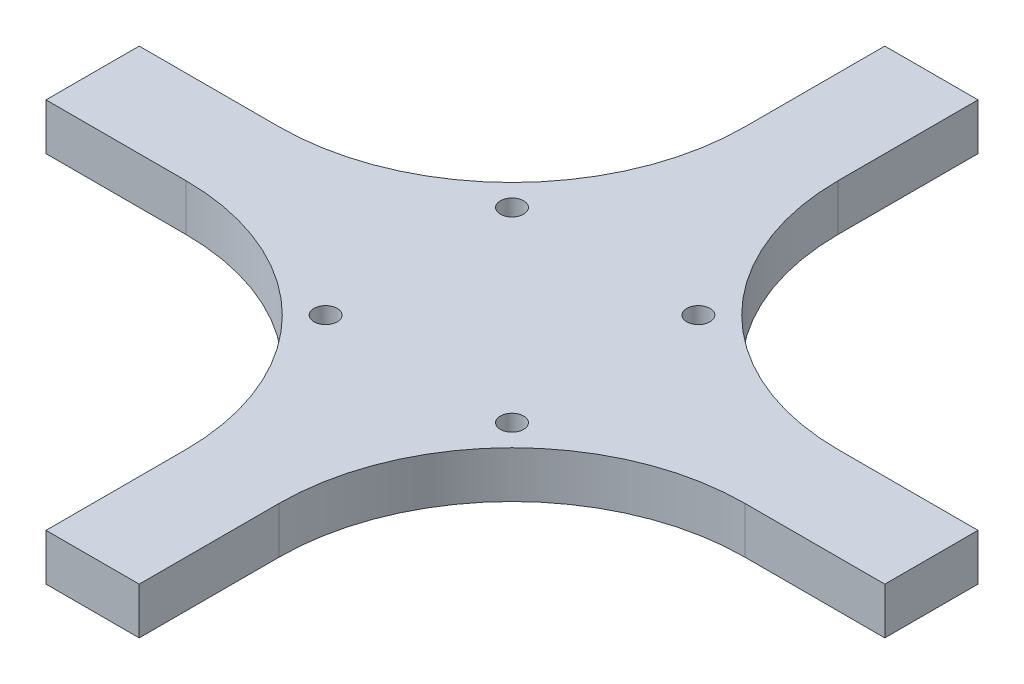
SolidWorks part; units mm, degrees
ref_plane "Front Plane" through (0, 0, 0) normal (0, 0, 1) x (1, 0, 0)
ref_plane "Top Plane" through (0, 0, 0) normal (0, 1, 0) x (1, 0, 0)
ref_plane "Right Plane" through (0, 0, 0) normal (1, 0, 0) x (0, 0, -1)
sketch "Sketch1" plane through (0, 0, 0) normal (0, 1, 0) x (1, 0, 0)
  line L0 (171.3318, 0) -> (-229.5995, 0) construction
  line L5 (0, 176.4778) -> (0, -135.7808) construction
  line L6 (-152.4, 25.4) -> (-228.6, 25.4)
  line L7 (-228.6, 25.4) -> (-228.6, -25.4)
  line L8 (-25.4, 152.4) -> (-25.4, 228.6)
  line L9 (-25.4, 228.6) -> (25.4, 228.6)
  line L10 (25.4, 152.4) -> (25.4, 228.6)
  line L11 (228.6, 25.4) -> (228.6, -25.4)
  line L12 (152.4, 25.4) -> (228.6, 25.4)
  line L13 (152.4, -25.4) -> (228.6, -25.4)
  line L14 (25.4, -152.4) -> (25.4, -228.6)
  line L15 (-25.4, -228.6) -> (25.4, -228.6)
  line L16 (-25.4, -152.4) -> (-25.4, -228.6)
  line L17 (-152.4, -25.4) -> (-228.6, -25.4)
  arc A0 (-152.4, 25.4) -> (-25.4, 152.4) centre (-152.4, 152.4) ccw
  arc A1 (152.4, 25.4) -> (25.4, 152.4) centre (152.4, 152.4) cw
  arc A2 (152.4, -25.4) -> (25.4, -152.4) centre (152.4, -152.4) ccw
  arc A3 (-152.4, -25.4) -> (-25.4, -152.4) centre (-152.4, -152.4) cw
  point P0 (0, 0)
  point P17 (0, 228.6)
  point P23 (228.6, 0)
  point P29 (-228.6, 0)
  dimension "D1" = 127
  dimension "D2" = 76.2
  dimension "D3" = 50.8
extrude "Boss-Extrude1" add sketch "Sketch1" along normal blind 25.4
sketch "Sketch2" plane through (0, 0, 0) normal (0, -1, 0) x (-1, 0, 0)
  line L0 (-13.97, 0) -> (13.97, 0) construction
  line L1 (50.8, 50.8) -> (-50.8, 50.8) construction
  line L2 (50.8, 50.8) -> (50.8, -50.8) construction
  line L3 (50.8, -50.8) -> (-50.8, -50.8) construction
  line L4 (-50.8, 50.8) -> (-50.8, -50.8) construction
  line L5 (50.8, 50.8) -> (-50.8, -50.8) construction
  line L6 (50.8, -50.8) -> (-50.8, 50.8) construction
  line L7 (0, 13.97) -> (0, -13.97) construction
  circle A0 centre (50.8, -50.8) radius 6.35
  circle A1 centre (50.8, 50.8) radius 6.35
  circle A2 centre (-50.8, 50.8) radius 6.35
  circle A3 centre (-50.8, -50.8) radius 6.35
  point P2 (0, 0)
  dimension "D1" = 12.7
  dimension "D2" = 101.6
  dimension "D3" = 101.6
extrude "Cut-Extrude1" cut sketch "Sketch2" against normal up to next contours A0 | A3 | A2 | A1
